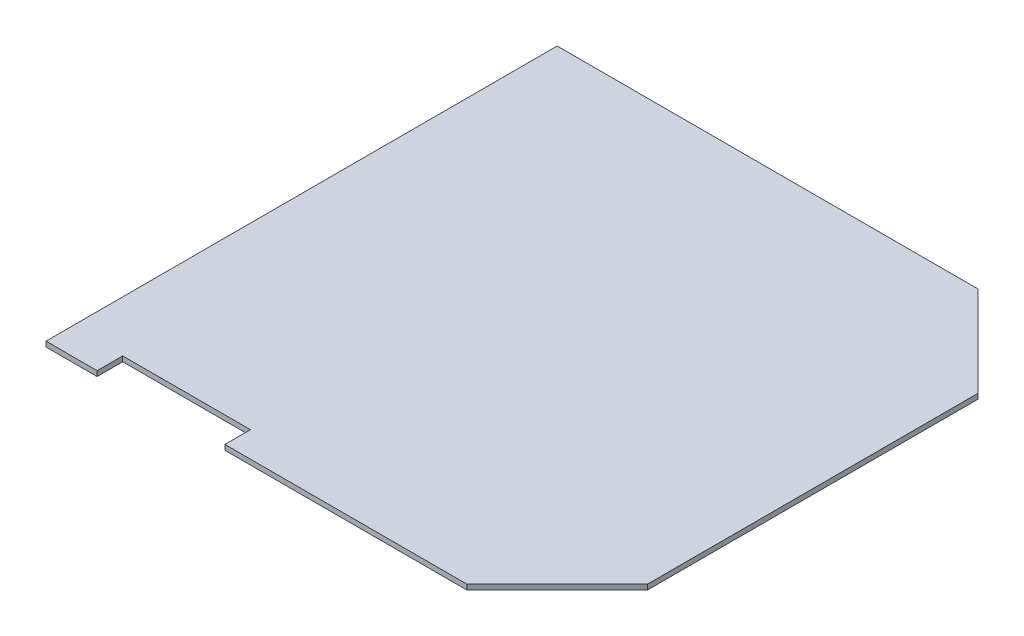
SolidWorks part; units mm, degrees
ref_plane "Front Plane" through (0, 0, 0) normal (0, 0, 1) x (1, 0, 0)
ref_plane "Top Plane" through (0, 0, 0) normal (0, 1, 0) x (1, 0, 0)
ref_plane "Right Plane" through (0, 0, 0) normal (1, 0, 0) x (0, 0, -1)
sketch "Sketch1" plane through (0, 0, 0) normal (0, 1, 0) x (1, 0, 0)
  line L0 (-82.3223, 100) -> (82.3223, 100)
  line L1 (82.3223, 100) -> (117.6777, 64.6447)
  line L2 (117.6777, 64.6447) -> (117.6777, -64.6447)
  line L3 (117.6777, -64.6447) -> (82.3223, -100)
  line L9 (-82.3223, -100) -> (-82.3223, 100)
  line L10 (-82.3223, -100) -> (82.3223, -100)
  point P9 (-82.3223, 0)
  point P11 (0, 100)
  point P14 (117.6777, 0)
  dimension "D1" = 200
  dimension "D2" = 200
  dimension "D3" = 45
  dimension "D4" = 45
  dimension "D5" = 50
extrude "Boss-Extrude1" add sketch "Sketch1" along normal blind 2
sketch "Sketch2" plane through (0, 2, 0) normal (0, 1, 0) x (1, 0, 0)
  line L0 (-82.3223, -100) -> (82.3223, -100) construction
  line L1 (-62.3223, -100) -> (-12.3223, -100)
  line L2 (-62.3223, -100) -> (-62.3223, -90)
  line L3 (-62.3223, -90) -> (-12.3223, -90)
  line L4 (-12.3223, -100) -> (-12.3223, -90)
  line L5 (-82.3223, 100) -> (-82.3223, -100) construction
  dimension "D1" = 10
  dimension "D2" = 50
  dimension "D3" = 20
extrude "Cut-Extrude1" cut sketch "Sketch2" against normal through all and the other way through all
